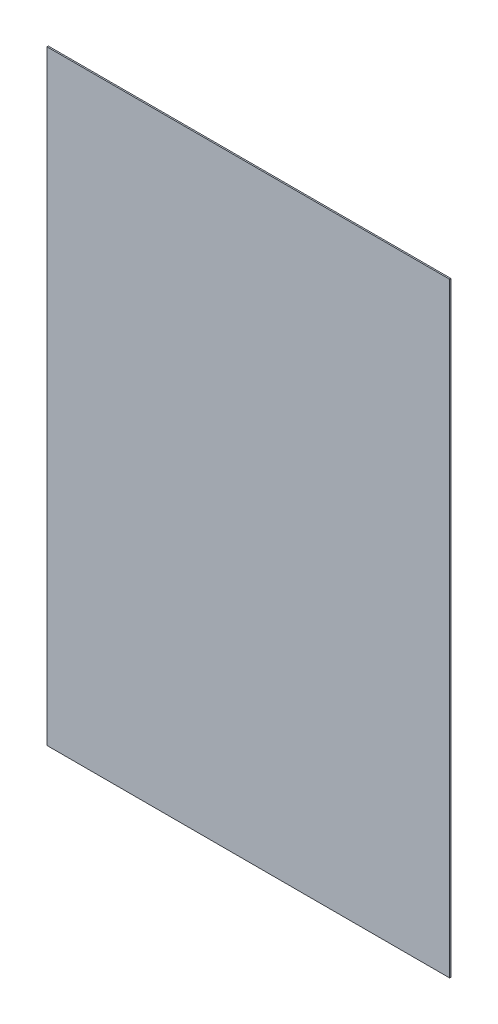
SolidWorks part; units mm, degrees
ref_plane "Plan de face" through (0, 0, 0) normal (0, 0, 1) x (1, 0, 0)
ref_plane "Plan de dessus" through (0, 0, 0) normal (0, 1, 0) x (1, 0, 0)
ref_plane "Plan de droite" through (0, 0, 0) normal (1, 0, 0) x (0, 0, -1)
sketch "Esquisse1" plane through (0, 0, 0) normal (0, 0, 1) x (1, 0, 0)
  line L1 (148.1862, 222.6616) -> (-148.1862, 222.6616)
  line L2 (148.1862, 222.6616) -> (148.1862, -222.6616)
  line L3 (148.1862, -222.6616) -> (-148.1862, -222.6616)
  line L4 (-148.1862, 222.6616) -> (-148.1862, -222.6616)
  line L5 (148.1862, 222.6616) -> (-148.1862, -222.6616) construction
  line L6 (148.1862, -222.6616) -> (-148.1862, 222.6616) construction
  point P0 (0, 0)
extrude "Boss.-Extru.1" add sketch "Esquisse1" along normal blind 1
sketch "Esquisse2" plane through (0, 0, 1) normal (0, 0, 1) x (1, 0, 0)
  line L0 (-87.5124, 23.8438) -> (-58.3258, 23.8438)
  line L1 (-58.3258, 23.8438) -> (-58.3258, 3.3438)
  line L2 (-58.3258, 3.3438) -> (-87.5124, 3.3438)
  line L3 (-13.7631, 23.8438) -> (-13.7631, 4.2871)
  line L4 (-13.7631, 4.2871) -> (-15.8534, 1.2823)
  line L5 (-15.8534, 1.2823) -> (-29.1792, 1.2823)
  line L6 (-29.1792, 1.2823) -> (-38.1937, 9.9049)
  line L7 (-38.1937, 9.9049) -> (-38.1937, 16.8233)
  line L8 (-38.1937, 16.8233) -> (-29.1792, 26.2476)
  line L9 (-29.1792, 26.2476) -> (-15.8534, 26.2476)
  line L10 (-15.8534, 26.2476) -> (-13.7631, 23.8438)
  line L11 (-9.7391, 58.5638) -> (1.2618, 58.5638)
  line L12 (1.2618, 58.5638) -> (3.117, 61.0374)
  line L13 (3.117, 61.0374) -> (3.117, 83.5852)
  line L14 (3.117, 83.5852) -> (-5.9888, 92.4415)
  line L15 (-5.9888, 92.4415) -> (-10.0285, 92.4415)
  line L16 (-10.0285, 92.4415) -> (-11.9758, 90.4393)
  line L17 (-11.9758, 90.4393) -> (-11.9758, 61.0866)
  line L18 (-11.9758, 61.0866) -> (-9.7391, 58.5638)
  line L19 (-5.9888, 119.9211) -> (11.0041, 119.9211)
  dimension "D1" = 20.5
  dimension "D2" = 24.9652
  dimension "D3" = 24.4305
  dimension "D4" = 15.0928
  dimension "D5" = 33.8777
  dimension "D6" = 27.4797
  dimension "D7" = 7.8871
